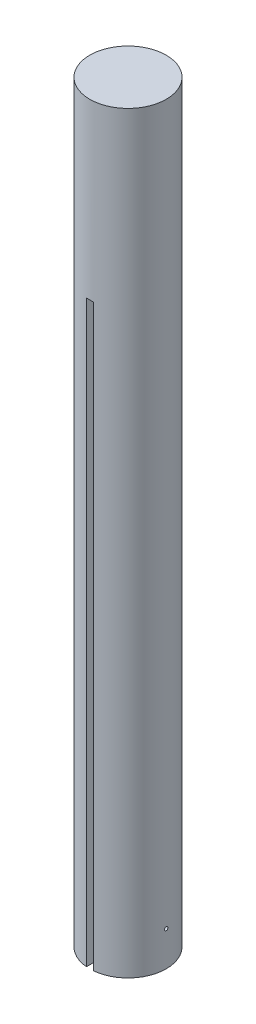
SolidWorks part; units mm, degrees
ref_plane "Front Plane" through (0, 0, 0) normal (0, 0, 1) x (1, 0, 0)
ref_plane "Top Plane" through (0, 0, 0) normal (0, 1, 0) x (1, 0, 0)
ref_plane "Right Plane" through (0, 0, 0) normal (1, 0, 0) x (0, 0, -1)
sketch "Sketch1" plane through (0, 0, 0) normal (0, 1, 0) x (1, 0, 0)
  circle A0 centre (0, 0) radius 11
extrude "Boss-Extrude1" add sketch "Sketch1" along normal blind 216.6667 contours A0
sketch "Sketch2" plane through (0, 0, 0) normal (0, 1, 0) x (1, 0, 0)
  circle A0 centre (0, 0) radius 6.8
sketch "Sketch6" plane through (0, 0, 0) normal (0, 1, 0) x (1, 0, 0)
  circle A0 centre (0, 0) radius 7
extrude "Cut-Extrude3" cut sketch "Sketch6" along normal blind 20
sketch "Sketch7" plane through (0, 0, 0) normal (1, 0, 0) x (0, 0, -1)
  line L1 (0, 12.1) -> (0, -12.1) construction
  circle A0 centre (0, 10) radius 0.5
extrude "Cut-Extrude4" cut sketch "Sketch7" against normal through all both and the other way through all
sketch "Sketch10" plane through (0, 0, 0) normal (0, 0, 1) x (1, 0, 0)
  line L1 (0, -12.1) -> (0, 12.1) construction
  circle A0 centre (0, 5) radius 0.5
extrude "Cut-Extrude5" cut sketch "Sketch10" against normal through all both and the other way through all
sketch "Sketch11" plane through (0, 0, 0) normal (0, 0, 1) x (1, 0, 0)
  line L0 (12.1, 0) -> (-12.1, 0) construction
  line L7 (11, 216.6667) -> (-11, 216.6667) construction
  line L9 (-1, 216.6667) -> (1, 216.6667)
  line L10 (-1, 216.6667) -> (-1, 0)
  line L11 (1, 216.6667) -> (1, 0)
  line L12 (-1, 0) -> (1, 0)
  point P7 (-1.0266, 0)
  point P10 (0.9737, 0)
extrude "Cut-Extrude6" cut sketch "Sketch11" against normal through all both and the other way through all
sketch "Sketch16" plane through (0, 0, 0) normal (0, 1, 0) x (1, 0, 0)
  circle A0 centre (0, 0) radius 11
extrude "Boss-Extrude4" add sketch "Sketch16" against normal blind 50 from surface at 216.6667 starting at face at (-6, 216.6667, 0)
equation "\"V\"=0"
